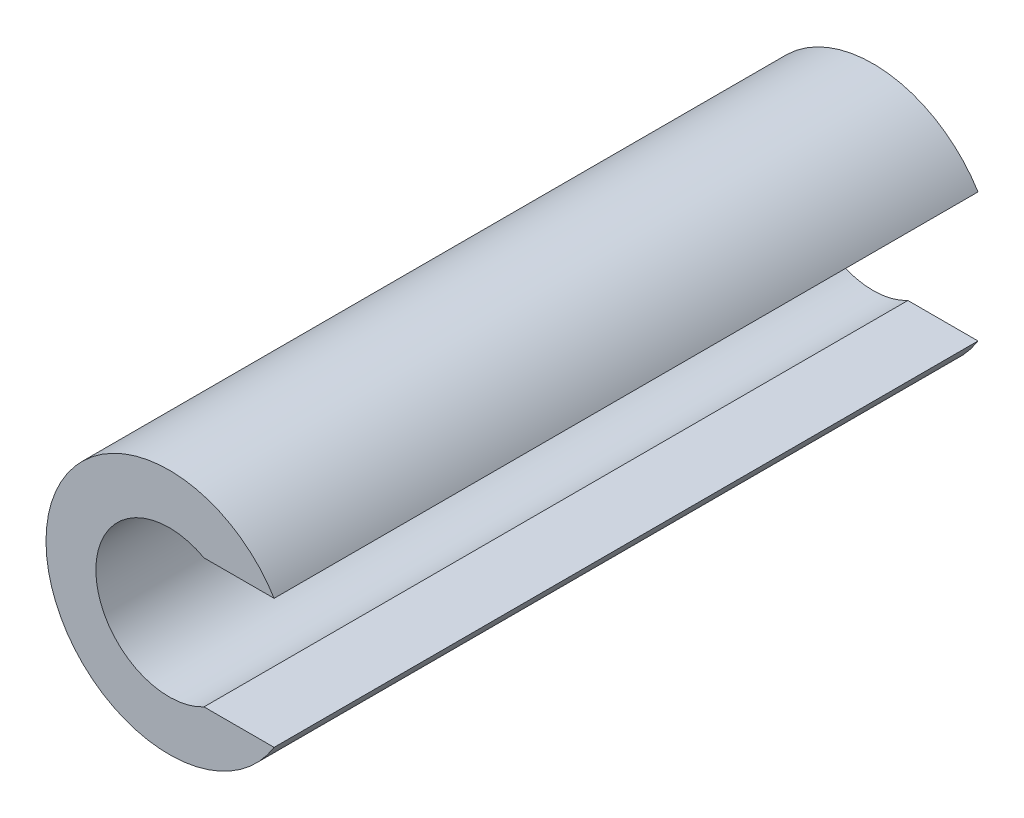
SolidWorks part; units mm, degrees
ref_plane "Front Plane" through (0, 0, 0) normal (0, 0, 1) x (1, 0, 0)
ref_plane "Top Plane" through (0, 0, 0) normal (0, 1, 0) x (1, 0, 0)
ref_plane "Right Plane" through (0, 0, 0) normal (1, 0, 0) x (0, 0, -1)
sketch "Sketch1" plane through (0, 0, 0) normal (0, 0, 1) x (1, 0, 0)
  circle A0 centre (0, 0) radius 10.5
  circle A1 centre (0, 0) radius 6.25
extrude "Sleeve" add sketch "Sketch1" along normal blind 60
sketch "Sketch2" plane through (0, 0, 0) normal (0, 0, 1) x (1, 0, 0)
  line L0 (0, -5.5) -> (12, -5.5)
  line L1 (12, -5.5) -> (12, 5.5)
  line L2 (12, 5.5) -> (0, 5.5)
  line L3 (0, 5.5) -> (0, -5.5)
extrude "Clip_opening" cut sketch "Sketch2" against normal through all and the other way through all
